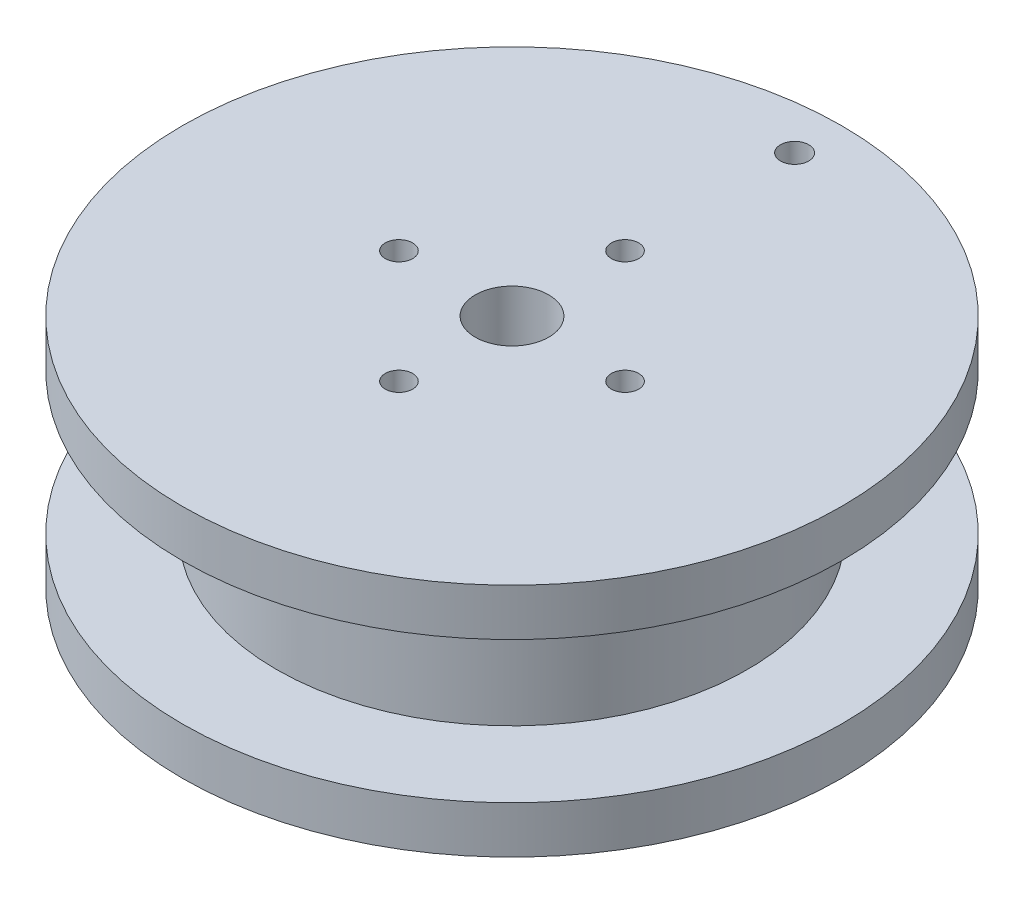
SolidWorks part; units mm, degrees
ref_plane "Front Plane" through (0, 0, 0) normal (0, 0, 1) x (1, 0, 0)
ref_plane "Top Plane" through (0, 0, 0) normal (0, 1, 0) x (1, 0, 0)
ref_plane "Right Plane" through (0, 0, 0) normal (1, 0, 0) x (0, 0, -1)
sketch "Sketch1" plane through (0, 0, 0) normal (1, 0, 0) x (0, 0, -1)
  line L1 (0, 0) -> (25, 0)
  line L2 (0, 0) -> (0, 15)
  line L3 (0, 15) -> (25, 15)
  line L4 (25, 0) -> (25, 15)
  line L5 (0, 15) -> (35, 15)
  line L6 (0, 15) -> (0, 20)
  line L7 (0, 20) -> (35, 20)
  line L8 (35, 15) -> (35, 20)
  line L9 (0, 0) -> (35, 0)
  line L10 (0, 0) -> (0, -5)
  line L11 (0, -5) -> (35, -5)
  line L12 (35, 0) -> (35, -5)
  dimension "D1" = 25
  dimension "D2" = 35
  dimension "D3" = 35
  dimension "D4" = 15
  dimension "D5" = 5
  dimension "D6" = 5
revolve "Revolve1" add sketch "Sketch1" angle 360 about L2
sketch "Sketch2" plane through (0, 20, 0) normal (0, 1, 0) x (1, 0, 0)
  circle A0 centre (0, 0) radius 15
  circle A1 centre (0, 0) radius 3.9
  circle A2 centre (0, 0) radius 12
  circle A3 centre (0, 12) radius 1.45
  circle A4 centre (12, 0) radius 1.45
  circle A5 centre (0, -12) radius 1.45
  circle A6 centre (-12, 0) radius 1.45
  point P16 (0, 0)
  dimension "D1" = 30
  dimension "D2" = 7.8
  dimension "D3" = 24
  dimension "D4" = 2.9
  dimension "D5" = 4
extrude "Cut-Extrude1" cut sketch "Sketch2" against normal blind 53 contours A2 A3 | A2 A3 | A2 A4 | A2 A4 | A2 A5 | A2 A5 | A2 A6 | A2 A6 | A1
sketch "Sketch3" plane through (0, 20, 0) normal (0, 1, 0) x (1, 0, 0)
  circle A0 centre (0, 30) radius 1.5
  dimension "D1" = 3
  dimension "D2" = 30
extrude "Cut-Extrude2" cut sketch "Sketch3" against normal blind 53
